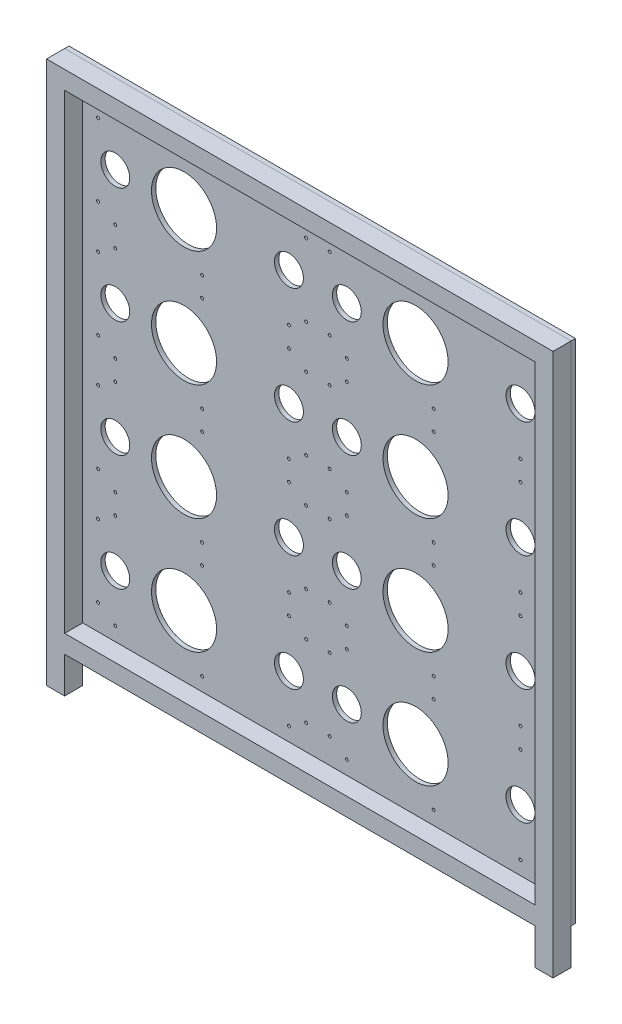
SolidWorks part; units mm, degrees
material "1060 Alloy"
ref_plane "Front Plane" through (0, 0, 0) normal (0, 0, 1) x (1, 0, 0)
ref_plane "Top Plane" through (0, 0, 0) normal (0, 1, 0) x (1, 0, 0)
ref_plane "Right Plane" through (0, 0, 0) normal (1, 0, 0) x (0, 0, -1)
sketch "Sketch8" plane through (0, 0, 0) normal (0, 0, 1) x (1, 0, 0)
  line L0 (0, 350) -> (0, 0) construction
  line L1 (-350, 350) -> (350, 350)
  line L2 (-350, 350) -> (-350, -350)
  line L3 (-350, -350) -> (350, -350)
  line L4 (350, 350) -> (350, -350)
  line L5 (0, 0) -> (0, -350) construction
  dimension "D1" = 700
  dimension "D2" = 700
extrude "Boss-Extrude7" add sketch "Sketch8" against normal blind 6
sketch "Sketch5" plane through (0, 0, 0) normal (0, 0, 1) x (1, 0, 0)
  line L0 (-350, 350) -> (350, 350)
  line L1 (-325, 325) -> (325, 325)
  line L2 (-325, 325) -> (-325, -325)
  line L3 (-325, -325) -> (325, -325)
  line L4 (325, 325) -> (325, -325)
  line L5 (350, 350) -> (350, -400)
  line L6 (350, -400) -> (325, -400)
  line L7 (325, -400) -> (325, -350)
  line L8 (-350, -350) -> (350, -350) construction
  line L9 (325, -350) -> (-325, -350)
  line L10 (-325, -350) -> (-325, -400)
  line L11 (-325, -400) -> (-350, -400)
  line L12 (-350, -400) -> (-350, 350)
  dimension "D1" = 25
  dimension "D2" = 25
  dimension "D3" = 25
  dimension "D4" = 25
  dimension "D5" = 750
extrude "Boss-Extrude8" add sketch "Sketch5" along normal blind 25 separate body
sketch "Sketch4" plane through (0, 0, 0) normal (0, 0, 1) x (1, 0, 0)
  line L0 (-303.75, 290) -> (-16.25, 290) construction
  line L1 (-303.75, 190) -> (-16.25, 190) construction
  line L2 (-16.25, 290) -> (-16.25, 190) construction
  line L3 (-160, 173.75) -> (-160, 240) construction
  line L4 (-160, 240) -> (-160, 306.25) construction
  line L5 (-303.75, 190) -> (-303.75, 290) construction
  line L6 (-303.75, 240) -> (-160, 240) construction
  line L7 (-160, 240) -> (-16.25, 240) construction
  line L8 (-160, 320) -> (-160, 306.25) construction
  line L9 (-320, 320) -> (0, 320) construction
  line L10 (-320, 320) -> (-320, 160) construction
  line L11 (-320, 160) -> (0, 160) construction
  line L12 (0, 320) -> (0, 160) construction
  line L13 (-160, 173.75) -> (-160, 160) construction
  line L14 (-303.75, 240) -> (-320, 240) construction
  line L15 (-16.25, 240) -> (0, 240) construction
  line L16 (0, 160) -> (0, 0) construction
  line L17 (-160, 306) -> (-160, 240) construction
  line L18 (-280, 174) -> (-40, 174) construction
  line L19 (-280, 174) -> (-280, 306) construction
  line L20 (-280, 306) -> (-40, 306) construction
  line L21 (-40, 174) -> (-40, 306) construction
  line L22 (-160, 240) -> (-160, 174) construction
  line L23 (-185, -80) -> (-185, -240) construction
  line L24 (-185, -240) -> (135, -240) construction
  circle A0 centre (-303.75, 290) radius 2
  circle A1 centre (-303.75, 190) radius 2
  circle A2 centre (-160, 306.25) radius 2
  circle A3 centre (-16.25, 290) radius 2
  circle A4 centre (-160, 173.75) radius 2
  circle A5 centre (-16.25, 190) radius 2
  circle A6 centre (-280, 174) radius 2
  circle A7 centre (-280, 306) radius 2
  circle A8 centre (-40, 306) radius 2
  circle A9 centre (-40, 174) radius 2
  circle A10 centre (40, 174) radius 2
  circle A11 centre (16.25, 190) radius 2
  circle A12 centre (40, 240) radius 20
  circle A13 centre (16.25, 290) radius 2
  circle A14 centre (40, 306) radius 2
  circle A15 centre (135, 240) radius 45
  circle A16 centre (160, 306.25) radius 2
  circle A17 centre (160, 173.75) radius 2
  circle A18 centre (280, 174) radius 2
  circle A19 centre (303.75, 190) radius 2
  circle A20 centre (280, 240) radius 20
  circle A21 centre (280, 306) radius 2
  circle A22 centre (303.75, 290) radius 2
  circle A23 centre (40, 14) radius 2
  circle A24 centre (16.25, 30) radius 2
  circle A25 centre (40, 80) radius 20
  circle A26 centre (16.25, 130) radius 2
  circle A27 centre (40, 146) radius 2
  circle A28 centre (135, 80) radius 45
  circle A29 centre (160, 146.25) radius 2
  circle A30 centre (160, 13.75) radius 2
  circle A31 centre (280, 14) radius 2
  circle A32 centre (303.75, 30) radius 2
  circle A33 centre (280, 80) radius 20
  circle A34 centre (280, 146) radius 2
  circle A35 centre (303.75, 130) radius 2
  circle A36 centre (40, -146) radius 2
  circle A37 centre (16.25, -130) radius 2
  circle A38 centre (40, -80) radius 20
  circle A39 centre (16.25, -30) radius 2
  circle A40 centre (40, -14) radius 2
  circle A41 centre (135, -80) radius 45
  circle A42 centre (160, -13.75) radius 2
  circle A43 centre (160, -146.25) radius 2
  circle A44 centre (280, -146) radius 2
  circle A45 centre (303.75, -130) radius 2
  circle A46 centre (280, -80) radius 20
  circle A47 centre (280, -14) radius 2
  circle A48 centre (-280, 240) radius 20
  circle A49 centre (-185, 240) radius 45
  circle A50 centre (-40, 240) radius 20
  circle A51 centre (303.75, -30) radius 2
  circle A52 centre (40, -306) radius 2
  circle A53 centre (16.25, -290) radius 2
  circle A54 centre (40, -240) radius 20
  circle A55 centre (16.25, -190) radius 2
  circle A56 centre (40, -174) radius 2
  circle A57 centre (135, -240) radius 45
  circle A58 centre (160, -173.75) radius 2
  circle A59 centre (160, -306.25) radius 2
  circle A60 centre (280, -306) radius 2
  circle A61 centre (303.75, -290) radius 2
  circle A62 centre (280, -240) radius 20
  circle A63 centre (280, -174) radius 2
  circle A64 centre (303.75, -190) radius 2
  circle A65 centre (-280, 14) radius 2
  circle A66 centre (-303.75, 30) radius 2
  circle A67 centre (-280, 80) radius 20
  circle A68 centre (-303.75, 130) radius 2
  circle A69 centre (-280, 146) radius 2
  circle A70 centre (-185, 80) radius 45
  circle A71 centre (-160, 146.25) radius 2
  circle A72 centre (-160, 13.75) radius 2
  circle A73 centre (-40, 14) radius 2
  circle A74 centre (-16.25, 30) radius 2
  circle A75 centre (-40, 80) radius 20
  circle A76 centre (-40, 146) radius 2
  circle A77 centre (-16.25, 130) radius 2
  circle A78 centre (-280, -146) radius 2
  circle A79 centre (-303.75, -130) radius 2
  circle A80 centre (-280, -80) radius 20
  circle A81 centre (-303.75, -30) radius 2
  circle A82 centre (-280, -14) radius 2
  circle A83 centre (-185, -80) radius 45
  circle A84 centre (-160, -13.75) radius 2
  circle A85 centre (-160, -146.25) radius 2
  circle A86 centre (-40, -146) radius 2
  circle A87 centre (-16.25, -130) radius 2
  circle A88 centre (-40, -80) radius 20
  circle A89 centre (-40, -14) radius 2
  circle A90 centre (-16.25, -30) radius 2
  circle A91 centre (-280, -306) radius 2
  circle A92 centre (-303.75, -290) radius 2
  circle A93 centre (-280, -240) radius 20
  circle A94 centre (-303.75, -190) radius 2
  circle A95 centre (-280, -174) radius 2
  circle A96 centre (-185, -240) radius 45
  circle A97 centre (-160, -173.75) radius 2
  circle A98 centre (-160, -306.25) radius 2
  circle A99 centre (-40, -306) radius 2
  circle A100 centre (-16.25, -290) radius 2
  circle A101 centre (-40, -240) radius 20
  circle A102 centre (-40, -174) radius 2
  circle A103 centre (-16.25, -190) radius 2
  dimension "D1" = 4
  dimension "D14" = 40
  dimension "D15" = 90
  dimension "D17" = 40
  dimension "D6" = 4
  dimension "D2" = 16.25
  dimension "D3" = 160
  dimension "D4" = 320
  dimension "D5" = 30
  dimension "D9" = 160
  dimension "D10" = 2
  dimension "D11" = 132.5
  dimension "D12" = 287.5
  dimension "D13" = 40
  dimension "D16" = 40
  dimension "D18" = 135
  dimension "D7" = 40
  dimension "D8" = 14
  dimension "D20" = 160
  dimension "D19" = 4
extrude "Cut-Extrude1" cut sketch "Sketch4" against normal through all
